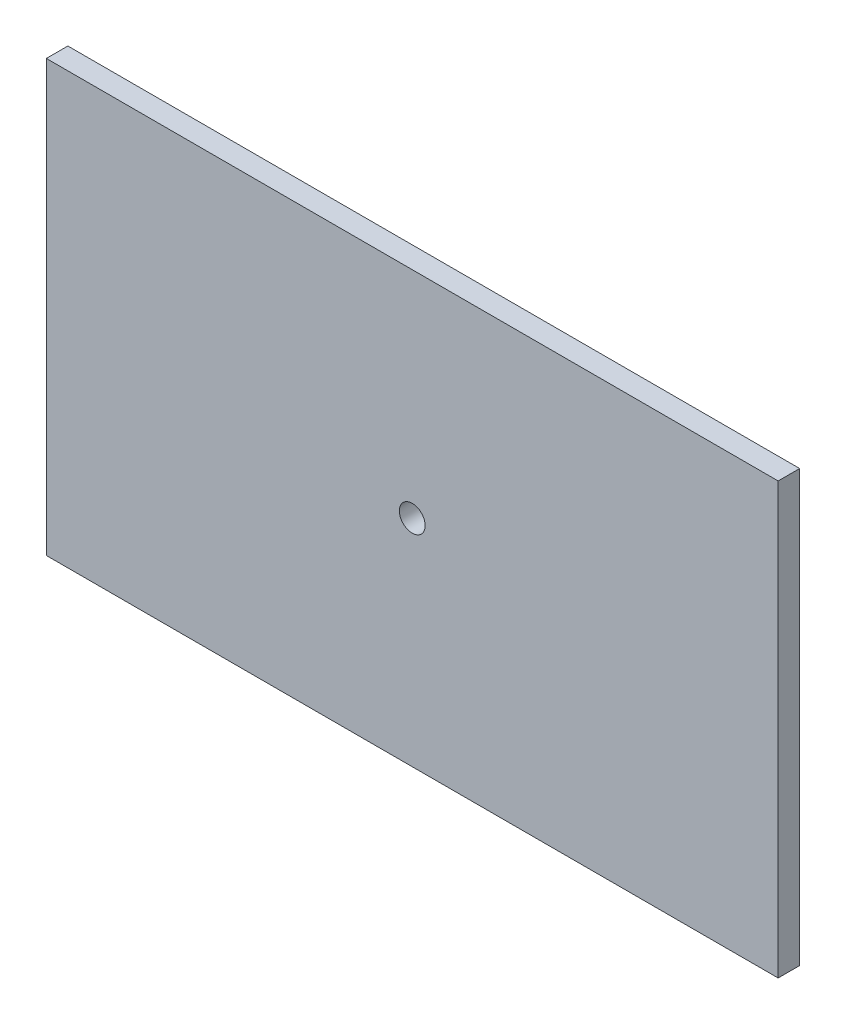
SolidWorks part; units mm, degrees
ref_plane "前视基准面" through (0, 0, 0) normal (0, 0, 1) x (1, 0, 0)
ref_plane "上视基准面" through (0, 0, 0) normal (0, 1, 0) x (1, 0, 0)
ref_plane "右视基准面" through (0, 0, 0) normal (1, 0, 0) x (0, 0, -1)
sketch "草图1" plane through (0, 0, 0) normal (0, 0, 1) x (1, 0, 0)
  line L1 (170, -100) -> (-170, -100)
  line L2 (170, -100) -> (170, 100)
  line L3 (170, 100) -> (-170, 100)
  line L4 (-170, -100) -> (-170, 100)
  line L5 (170, -100) -> (-170, 100) construction
  line L6 (170, 100) -> (-170, -100) construction
  point P0 (0, 0)
  dimension "D1" = 340
  dimension "D2" = 200
extrude "凸台-拉伸1" add sketch "草图1" along normal blind 10
sketch "草图2" plane through (0, 0, 10) normal (0, 0, 1) x (1, 0, 0)
  line L0 (0, 100) -> (0, 0) construction
  line L1 (170, 100) -> (-170, 100) construction
  line L2 (0, 0) -> (170, 0) construction
  line L3 (170, -100) -> (170, 100) construction
  circle A0 centre (0, 0) radius 6
  dimension "D1" = 12
extrude "切除-拉伸1" cut sketch "草图2" against normal through all
